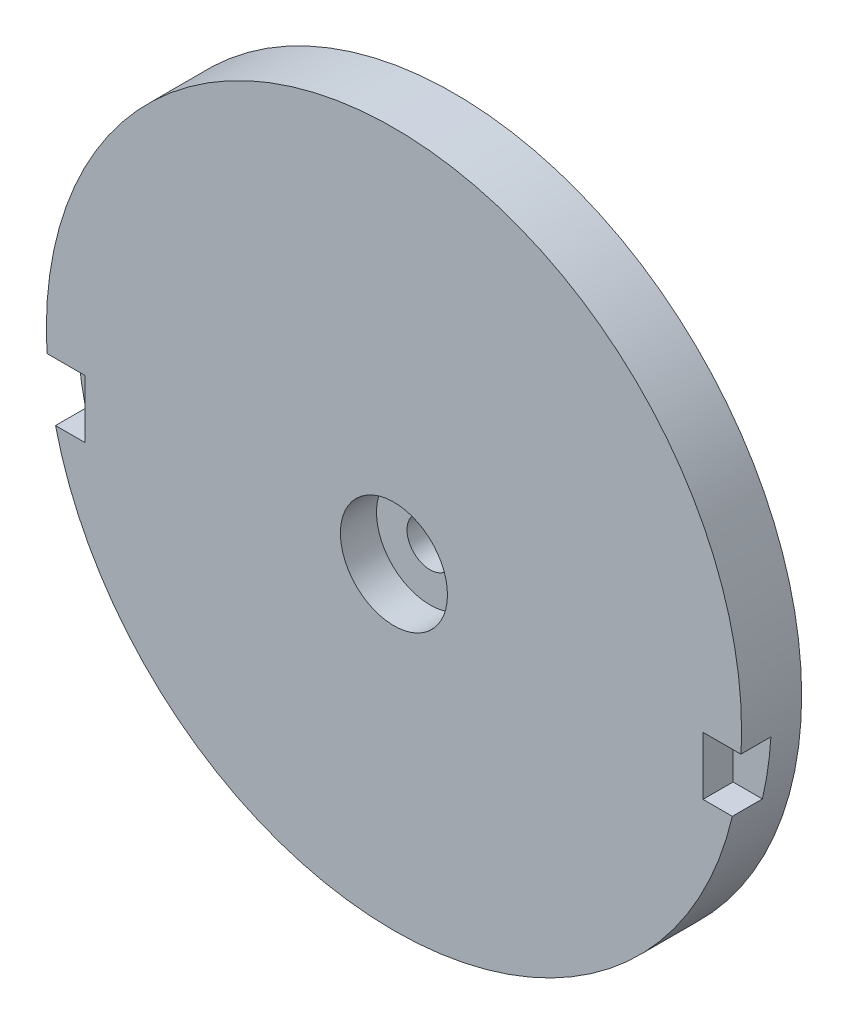
SolidWorks part; units mm, degrees
material "PLA"
ref_plane "Front Plane" through (0, 0, 0) normal (0, 0, 1) x (1, 0, 0)
ref_plane "Top Plane" through (0, 0, 0) normal (0, 1, 0) x (1, 0, 0)
ref_plane "Right Plane" through (0, 0, 0) normal (1, 0, 0) x (0, 0, -1)
sketch "Sketch1" plane through (0, 0, 0) normal (0, 0, 1) x (1, 0, 0)
  circle A0 centre (0, 0) radius 73.406
  dimension "D1" = 146.812
extrude "Boss-Extrude1" add sketch "Sketch1" against normal blind 12.7
sketch "Sketch2" plane through (0, 0, 0) normal (0, 0, 1) x (1, 0, 0)
  line L0 (0, 27.455) -> (0, -34.5966) construction
  line L11 (-73.406, 0) -> (77.02, 0) construction
  line L13 (73.406, -4.4958) -> (67.31, -4.4958)
  line L14 (-73.406, 0) -> (-67.31, 0)
  line L16 (-73.406, 0) -> (-73.406, -4.4958)
  line L17 (-73.406, -4.4958) -> (-67.31, -4.4958)
  line L18 (-67.31, 0) -> (-67.31, -4.4958)
  line L19 (-73.406, -4.4958) -> (-67.31, -4.4958)
  line L23 (67.31, 0) -> (67.31, -4.4958)
  line L24 (73.406, 0) -> (67.31, 0)
  line L25 (73.406, 0) -> (73.406, -4.4958)
  line L30 (71.4661, -4.4958) -> (65.2685, -4.4958)
  line L35 (65.2685, -16.764) -> (65.2685, -4.4958)
  line L36 (-71.4661, -16.764) -> (-65.2685, -16.764)
  line L37 (-71.4661, -16.764) -> (-71.4661, -4.4958)
  line L38 (-71.4661, -4.4958) -> (-65.2685, -4.4958)
  line L39 (-65.2685, -16.764) -> (-65.2685, -4.4958)
  line L40 (71.4661, -16.764) -> (65.2685, -16.764)
  line L41 (71.4661, -16.764) -> (71.4661, -4.4958)
  circle A0 centre (0, -6.35) radius 4.8514
  circle A2 centre (0, 0) radius 73.406 construction
  circle A3 centre (0, 0) radius 73.406
  circle M11 centre (0, 0) radius 73.406
  dimension "D2" = 9.7028
  dimension "D1" = 6.35
  dimension "D3" = 4.4958
  dimension "D4" = 6.096
  dimension "D5" = 6.1976
  dimension "D6" = 12.2682
extrude "Cut-Extrude1" cut sketch "Sketch2" against normal blind 6.35 contours L36 L39 L38 L19 L37 | L37 L17 M11 | L40 L41 L13 L30 L35 | L41 L13 M11
sketch "Sketch3" plane through (0, 0, 0) normal (0, 0, 1) x (1, 0, 0)
  circle A0 centre (0, -6.35) radius 11.303
  dimension "D1" = 22.606
  dimension "D2" = 6.35
extrude "Cut-Extrude2" cut sketch "Sketch3" against normal blind 7.62 contours A0
sketch "Sketch4" plane through (0, 0, 0) normal (0, 0, 1) x (1, 0, 0)
  circle A0 centre (0, -6.35) radius 4.8641
  dimension "D1" = 9.7282
extrude "Cut-Extrude3" cut sketch "Sketch4" against normal through all
